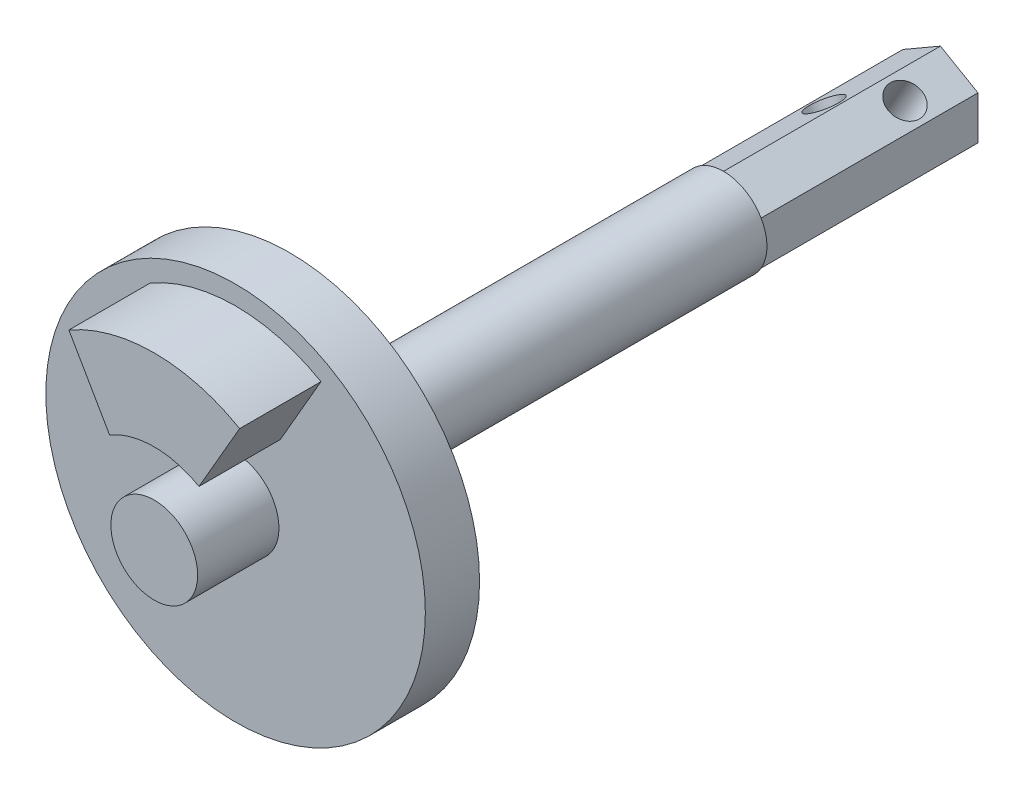
SolidWorks part; units mm, degrees
ref_plane "Front Plane" through (0, 0, 0) normal (0, 0, 1) x (1, 0, 0)
ref_plane "Top Plane" through (0, 0, 0) normal (0, 1, 0) x (1, 0, 0)
ref_plane "Right Plane" through (0, 0, 0) normal (1, 0, 0) x (0, 0, -1)
sketch "Sketch1" plane through (0, 0, 0) normal (0, 0, 1) x (1, 0, 0)
  circle A0 centre (0, 0) radius 17.5
  dimension "D1" = 35
extrude "Boss-Extrude1" add sketch "Sketch1" along normal mid plane 5
sketch "Sketch2" plane through (0, 0, 2.5) normal (0, 0, 1) x (1, 0, 0)
  line L3 (0, 0) -> (0, 11) construction
  line L4 (7.875, 13.6399) -> (4.125, 7.1447)
  line L5 (-4.125, 7.1447) -> (-7.875, 13.6399)
  arc A1 (4.125, 7.1447) -> (-4.125, 7.1447) centre (0, 0) ccw
  arc A6 (-7.875, 13.6399) -> (7.875, 13.6399) centre (0, 0) cw
  circle A7 centre (0, 0) radius 17.5 construction
  dimension "D2" = 7.5
  dimension "D3" = 1.75
  dimension "D1" = 30
extrude "Boss-Extrude2" add sketch "Sketch2" along normal blind 7.5
sketch "Sketch3" plane through (0, 0, 2.5) normal (0, 0, 1) x (1, 0, 0)
  circle A0 centre (0, 0) radius 4
extrude "Boss-Extrude3" add sketch "Sketch3" along normal blind 7.5
sketch "Sketch7" plane through (0, 0, -2.5) normal (0, 0, -1) x (-1, 0, 0)
  circle A0 centre (0, 0) radius 4
extrude "Boss-Extrude4" add sketch "Sketch7" along normal blind 40
sketch "Sketch9" plane through (0, 0, -42.5) normal (0, 0, -1) x (-1, 0, 0)
  line L0 (0, 4) -> (0, -4) construction
  line L1 (-3.4641, -2) -> (3.4641, 2) construction
  line L2 (-3.4641, 2) -> (3.4641, -2) construction
  line L11 (0, 4) -> (-3.4641, 2)
  line L12 (-3.4641, 2) -> (-3.4641, -2)
  line L13 (-3.4641, -2) -> (0, -4)
  line L14 (0, -4) -> (3.4641, -2)
  line L15 (3.4641, -2) -> (3.4641, 2)
  line L16 (3.4641, 2) -> (0, 4)
  circle A0 centre (0, 0) radius 4 construction
  point P4 (0, 0)
  point P5 (0, 0)
  point P6 (0, 0)
  point P8 (0, 0)
  point P11 (0, 0)
  point P13 (0, 0)
  point P15 (0, 0)
  point P19 (0, 0)
  point P22 (0, 0)
extrude "Boss-Extrude5" add sketch "Sketch9" along normal blind 20
sketch "Sketch10" plane through (-1.7321, -3, 0) normal (-0.5, -0.866, 0) x (0.866, -0.5, 0)
  line L2 (0, -57.5) -> (0, -42.5) construction
  line L3 (2, -42.5) -> (-2, -42.5) construction
  circle A0 centre (0, -57.5) radius 1.55
extrude "Cut-Extrude1" cut sketch "Sketch10" against normal up to surface (6.9282 mm away) up to face at (1.7321, 3, -52.5)
sketch "Sketch11" plane through (1.7321, -3, 0) normal (-0.5, 0.866, 0) x (0, 0, 1)
  line L0 (-53.5, 0) -> (-42.5, 0) construction
  line L1 (-42.5, 2) -> (-42.5, -2) construction
  circle A1 centre (-53.5, 0) radius 1.55
extrude "Cut-Extrude4" cut sketch "Sketch11" along normal up to surface (6.9282 mm away) up to face at (-1.7321, 3, -52.5)
